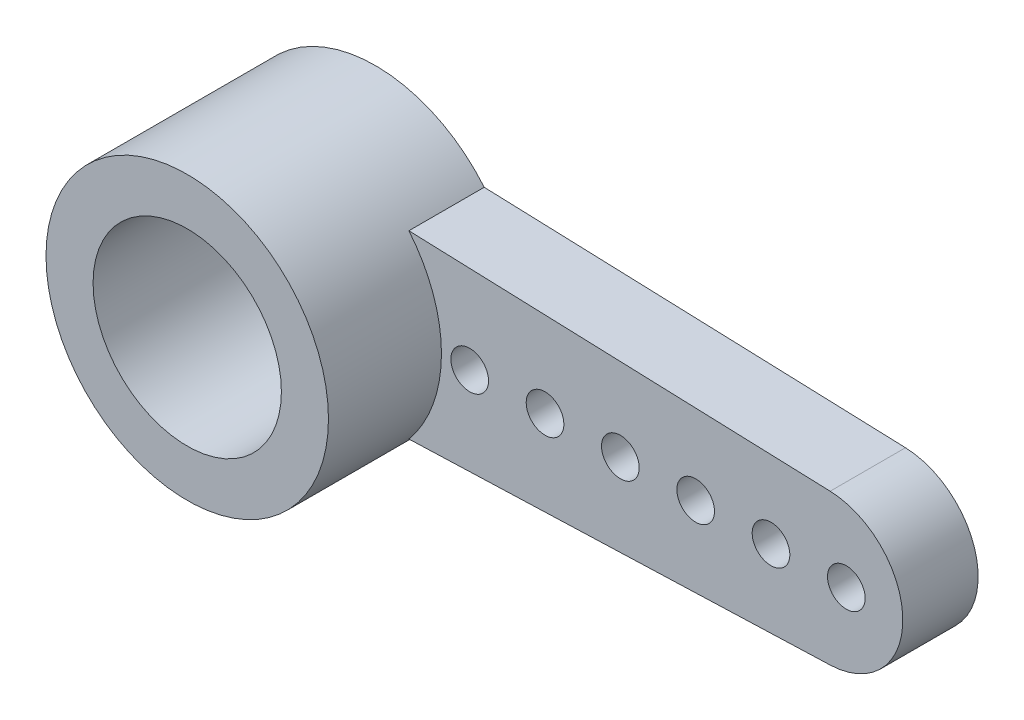
SolidWorks part; units mm, degrees
ref_plane "Спереди" through (0, 0, 0) normal (0, 0, 1) x (1, 0, 0)
ref_plane "Сверху" through (0, 0, 0) normal (0, 1, 0) x (1, 0, 0)
ref_plane "Справа" through (0, 0, 0) normal (1, 0, 0) x (0, 0, -1)
sketch "Эскиз1" plane through (0, 0, 0) normal (0, 0, 1) x (1, 0, 0)
  line L0 (0, 0) -> (-14, 0)
  line L1 (-14.0708, 1.9987) -> (0, 2.4974)
  line L2 (-14.0708, -1.9987) -> (0, -2.4974)
  line L4 (14.0708, -1.9987) -> (0, -2.4974)
  line L5 (14.0708, 1.9987) -> (0, 2.4974)
  circle A0 centre (0, 0) radius 3.75
  circle A1 centre (0, 0) radius 2.5
  arc A2 (-13.967, -1.9997) -> (-14.0708, 1.9987) centre (-14, 0) cw
  arc A3 (13.967, -1.9997) -> (14.0708, 1.9987) centre (14, 0) ccw
  dimension "D1" = 7.5
  dimension "D2" = 5
  dimension "D4" = 2
  dimension "D3" = 14
extrude "Бобышка-Вытянуть3" add sketch "Эскиз1" along normal blind 2
sketch "Эскиз2" plane through (0, 0, 2) normal (0, 0, 1) x (1, 0, 0)
  circle A0 centre (0, 0) radius 3.75
  circle A1 centre (0, 0) radius 2.5
  dimension "D1" = 5
extrude "Бобышка-Вытянуть5" add sketch "Эскиз2" along normal blind 3 separate body
sketch "Эскиз3" plane through (0, 0, 2) normal (0, 0, -1) x (-1, 0, 0)
  circle A0 centre (0, 0) radius 3.75
  circle A1 centre (0, 0) radius 2.5
extrude "Бобышка-Вытянуть6" add sketch "Эскиз3" along normal blind 2
sketch "Эскиз4" plane through (0, 0, 0) normal (0, 0, -1) x (-1, 0, 0)
  line L0 (-16, 0) -> (-14.5, 0)
  line L1 (-14.5, 0) -> (-12.5, 0)
  line L2 (-12.5, 0) -> (-10.5, 0)
  line L3 (-10.5, 0) -> (-8.5, 0)
  line L4 (-8.5, 0) -> (-6.5, 0)
  line L5 (-6.5, 0) -> (-4.5, 0)
  arc A0 (-14.0708, 1.9987) -> (-14.0708, -1.9987) centre (-14, 0) ccw construction
  circle A1 centre (-14.5, 0) radius 0.5
  circle A2 centre (-12.5, 0) radius 0.5
  circle A3 centre (-10.5, 0) radius 0.5
  circle A4 centre (-8.5, 0) radius 0.5
  circle A5 centre (-6.5, 0) radius 0.5
  circle A6 centre (-4.5, 0) radius 0.5
  circle A7 centre (4.5, 0) radius 0.5
  circle A8 centre (6.5, 0) radius 0.5
  circle A9 centre (8.5, 0) radius 0.5
  circle A10 centre (10.5, 0) radius 0.5
  circle A11 centre (12.5, 0) radius 0.5
  circle A12 centre (14.5, 0) radius 0.5
  dimension "D2" = 1
  dimension "D8" = 1
  dimension "D9" = 1
  dimension "D10" = 1
  dimension "D11" = 1
  dimension "D12" = 1
  dimension "D1" = 1.5
  dimension "D3" = 2
  dimension "D4" = 2
  dimension "D5" = 2
  dimension "D6" = 2
  dimension "D7" = 2
extrude "Вырез-Вытянуть1" cut sketch "Эскиз4" against normal blind 2
sketch "Эскиз5" plane through (0, 0, 0) normal (0, 0, -1) x (-1, 0, 0)
  circle A0 centre (0, 0) radius 2.5
extrude "Бобышка-Вытянуть7" add sketch "Эскиз5" against normal blind 1
sketch "Эскиз6" plane through (0, 0, 0) normal (0, 0, -1) x (-1, 0, 0)
  circle A0 centre (0, 0) radius 2.5
  dimension "D1" = 5
extrude "Вырез-Вытянуть2" cut sketch "Эскиз6" against normal blind 0.5
sketch "Эскиз7" plane through (0, 0, 0.5) normal (0, 0, -1) x (-1, 0, 0)
  circle A0 centre (0, 0) radius 1.25
  dimension "D1" = 2.5
extrude "Вырез-Вытянуть3" cut sketch "Эскиз7" against normal blind 5
sketch "Эскиз8" plane through (0, 0, 0.5) normal (0, 0, -1) x (-1, 0, 0)
  line L0 (-2.8252, -0.1999) -> (-2.8894, -0.2509)
  line L2 (17.0027, -3.75) -> (0, -3.75)
  line L3 (17.0027, -3.75) -> (17.0027, 3.75)
  line L4 (17.0027, 3.75) -> (0, 3.75)
  arc A0 (0, -3.75) -> (0, 3.75) centre (0, 0) ccw
  point P9 (0, -3.75)
extrude "Cut-Extrude1" cut sketch "Эскиз8" against normal through all both and the other way through all contours L4 A0 L2 L3
